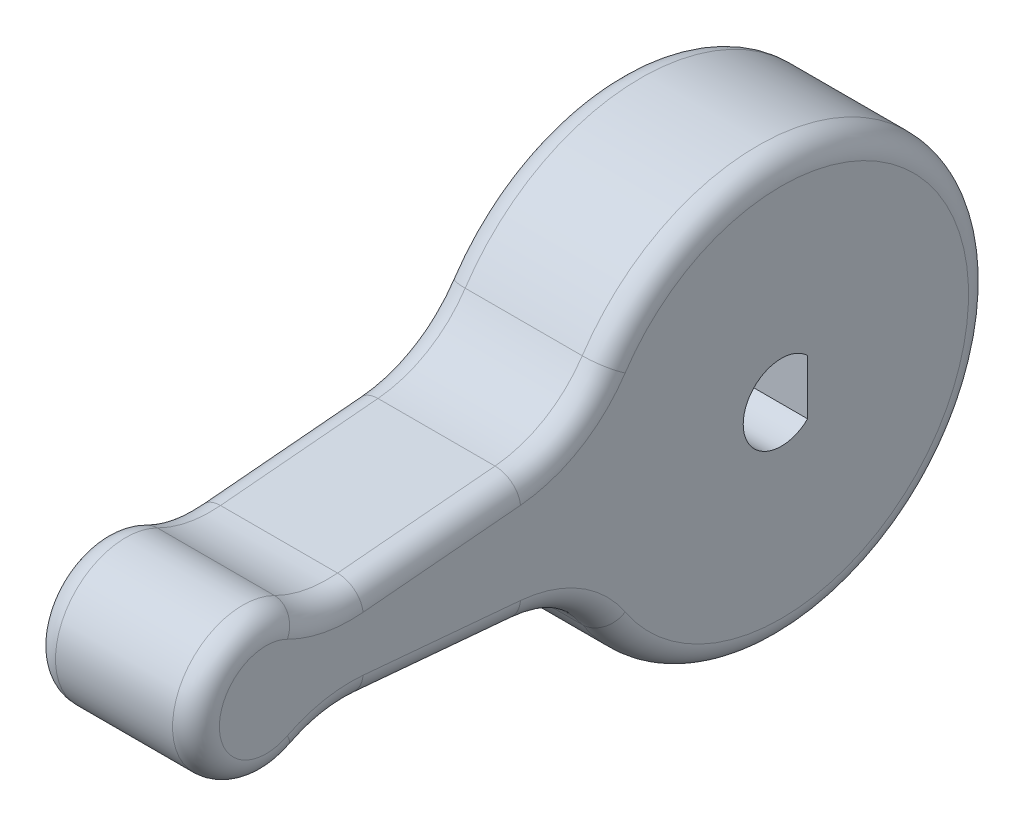
SolidWorks part; units mm, degrees
material "ABS"
ref_plane "Front Plane" through (0, 0, 0) normal (0, 0, 1) x (1, 0, 0)
ref_plane "Top Plane" through (0, 0, 0) normal (0, 1, 0) x (1, 0, 0)
ref_plane "Right Plane" through (0, 0, 0) normal (1, 0, 0) x (0, 0, -1)
sketch "Sketch1" plane through (0, 0, 0) normal (1, 0, 0) x (0, 0, -1)
  line L0 (1.125, -1.1726) -> (1.125, 1.1726)
  line L1 (-25, 0) -> (-22, 0) construction
  line L2 (-22, 0) -> (0, 0) construction
  line L3 (-19.7639, 2) -> (-8.4853, 3)
  line L4 (-19.7639, -2) -> (-8.4853, -3)
  line L5 (0, 0) -> (9, 0) construction
  line L6 (-1.625, 0) -> (1.125, 0) construction
  arc A0 (1.125, 1.1726) -> (1.125, -1.1726) centre (0, 0) ccw
  arc A1 (-8.4853, -3) -> (-8.4853, 3) centre (0, 0) ccw
  arc A2 (-19.7639, 2) -> (-19.7639, -2) centre (-22, 0) ccw
  dimension "D1" = 6
  dimension "D2" = 18
  dimension "D4" = 6
  dimension "D6" = 1.625
  dimension "D3" = 25
  dimension "D5" = 4
  dimension "D7" = 2.75
extrude "Boss-Extrude1" add sketch "Sketch1" along normal mid plane 7
fillet "Fillet1" radius 5 4 edges at (0, 2, 19.7639) (0, -3, 8.4853) (0, -2, 19.7639) (0, 3, 8.4853)
ref_plane "Plane1" through (0, 0, -9.125) normal (0, 0, 1) x (1, 0, 0)
hole_wizard "Hole1" positions "Sketch2" profile "Sketch3" legacy
sketch "Sketch2" plane through (0, 0, -9.125) normal (0, 0, 1) x (1, 0, 0)
  point P0 (0, 0)
sketch "Sketch3" plane through (0, 0, -9.125) normal (1, 0, 0) x (0, 1, 0)
  line L0 (0, 0) -> (0, 9)
  line L1 (0, 9) -> (1.25, 9)
  line L2 (1.25, 9) -> (1.25, 3)
  line L3 (1.25, 3) -> (1.75, 3)
  line L4 (1.75, 3) -> (1.75, 0)
  line L5 (1.75, 0) -> (0, 0)
  line L6 (0, 110) -> (0, -10) construction
  dimension "Diameter" = 2.5
  dimension "Depth" = 9
  dimension "C-Bore Diameter" = 3.5
  dimension "C-Bore Depth" = 3
fillet "Fillet2" radius 1 16 edges at (-3.5, -3.4408, 9.1105) (-3.5, -2.4588, 14.5891) (-3.5, -2.2307, 19.3361) (-3.5, 0, 25) (-3.5, 2.2307, 19.3361) (-3.5, 2.4588, 14.5891) (-3.5, 3.4408, 9.1105) (3.5, -3.4408, 9.1105) (3.5, -2.4588, 14.5891) (3.5, -2.2307, 19.3361) (3.5, 0, 25) (3.5, 2.2307, 19.3361) (3.5, 2.4588, 14.5891) (3.5, 3.4408, 9.1105) (-3.5, 0, -9) (3.5, 0, -9)
